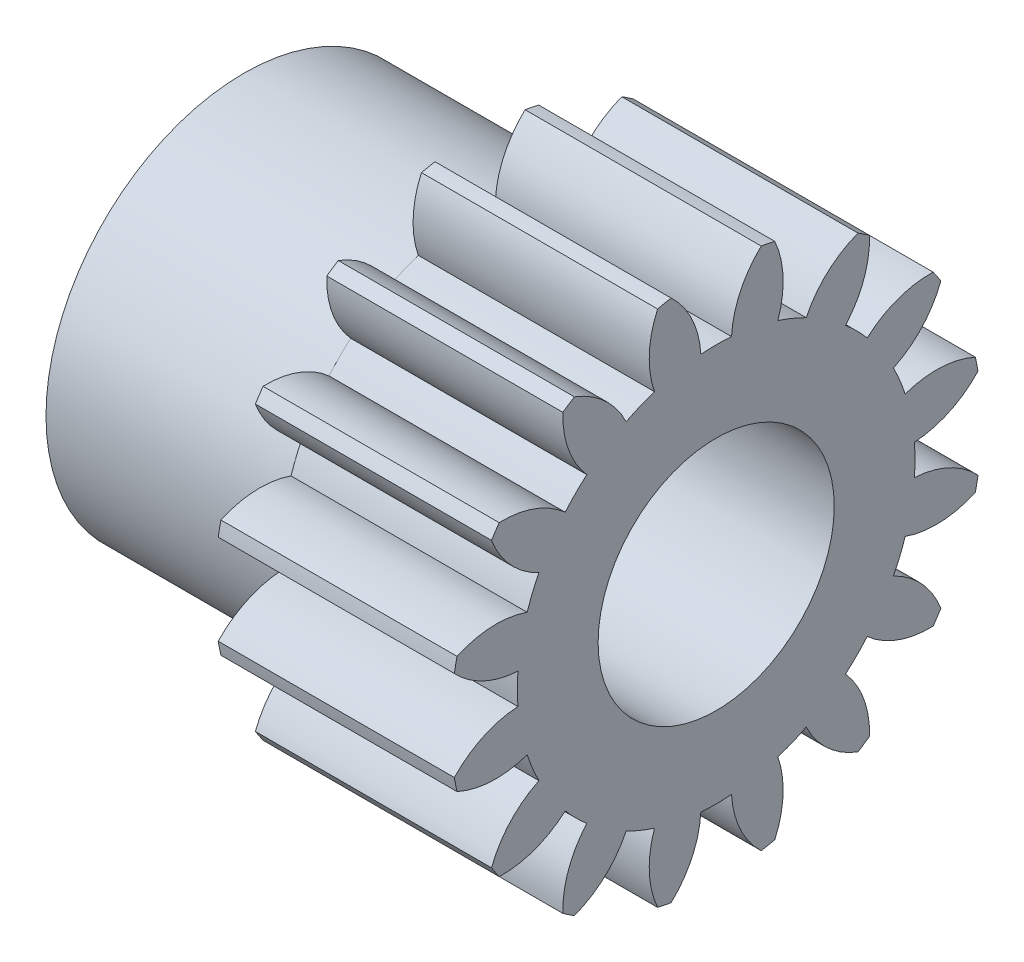
SolidWorks part; units mm, degrees
ref_plane "Plane1" through (0, 0, 0) normal (0, 0, 1) x (1, 0, 0)
ref_plane "Plane2" through (0, 0, 0) normal (0, 1, 0) x (1, 0, 0)
ref_plane "Plane3" through (0, 0, 0) normal (1, 0, 0) x (0, 0, -1)
sketch "HoldingSke" plane through (0, 0, 0) normal (0, 1, 0) x (1, 0, 0)
  line L0 (0, 0) -> (781.3135, -224.038)
  line L1 (-15, 0) -> (100, 0) construction
  line L2 (0, 0) -> (-2.1039, 2.3779)
  line L3 (0, 0) -> (-11.863, 4.5341)
  line L4 (0, 0) -> (8.3015, 2.3804)
  line L5 (0, 0) -> (-5.9497, -2.219)
  line L6 (0, 0) -> (-5.2639, -3.5516)
  line L7 (-2.1039, 2.3779) -> (-0.737, 8.5791)
  line L8 (-76.2, 54.61) -> (-69.596, 54.61)
  line L9 (-71.009, 38.7566) -> (-53.1078, 45.2721)
  line L10 (-76.2, 71.12) -> (104.1128, 71.12)
  line L11 (0, 0) -> (-6.35, 0)
  line L12 (-76.2, 101.6) -> (-76.1716, 101.6)
  line L13 (24.9733, 27.94) -> (52.9518, 28.4284)
  line L14 (24.9733, 27.94) -> (25.0241, 27.9398)
  line L15 (24.9733, 27.94) -> (100.4021, 29.52)
  circle A0 centre (0, 0) radius 3.175
  circle A1 centre (0, 0) radius 5.3213
  circle A2 centre (0, 0) radius 5.3213
  circle A3 centre (0, 0) radius 3.175
  dimension "MHD" = 10.6426
  dimension "Hub_dia" = 10.6426
  dimension "Bore" = 6.35
  dimension "MBD" = 6.35
  dimension "Num_teeth" = 16
  dimension "Pitch_radius" = 180.3128
  dimension "Pitch" = 812.8
  dimension "Width" = 6.35
  dimension "Overall_len" = 6.35
  dimension "Show_teeth" = 16
  dimension "Thickness" = 6.35
  dimension "OAL" = 6.3501
  dimension "T_dim" = 6.604
  dimension "Ap" = 20
  dimension "H" = 19.05
  dimension "Backlash" = 0.0284
  dimension "Addendum_fac" = 1
  dimension "Dedendum_fac" = 1.2
  dimension "Clearance_fac" = 0.2
  dimension "Dedendum_add" = 0.0508
sketch "BasProSke" plane through (0, 0, 0) normal (0, 1, 0) x (1, 0, 0)
  line L0 (-10, 0) -> (60, 0) construction
  line L1 (0, 0) -> (0, 7.1438)
  line L2 (0, 0) -> (6.35, 0)
  line L3 (6.35, 0) -> (6.35, 7.1438)
  line L4 (6.35, 7.1438) -> (0, 7.1438)
  dimension "Diameter" = 14.2875
  dimension "Thickness" = 6.35
revolve "Base-Revolve" add sketch "BasProSke" angle 360 about L0
sketch "TooCutSke" plane through (0, 0, 0) normal (1, 0, 0) x (0, 0, -1)
  line L1 (0, 0) -> (0, 107) construction
  line L2 (0, 0) -> (-0.6722, 6.3143) construction
  line L3 (0, 0) -> (-2.4676, 12.4052) construction
  line L4 (-0.6722, 6.3143) -> (-1.2338, 6.2026) construction
  arc A0 (0.4126, 5.3308) -> (-0.4126, 5.3308) centre (0, 0) ccw
  arc A1 (1.2345, 7.0621) -> (-1.2345, 7.0621) centre (0, 0) ccw
  circle A2 centre (0, 0) radius 6.35 construction
  circle A3 centre (0, 0) radius 5.967 construction
  arc A4 (-0.4126, 5.3308) -> (-1.2345, 7.0621) centre (-2.9486, 5.1876) ccw
  arc A5 (1.2345, 7.0621) -> (0.4126, 5.3308) centre (2.9486, 5.1876) ccw
  dimension "Root_dia" = 10.6934
  dimension "Overcut_dia" = 14.3383
  dimension "Pitch_dia" = 12.7
  dimension "Base_dia" = 11.9341
  dimension "Flank_rad" = 2.54
  dimension "Half_ang" = 11.25
  dimension "Half_CT" = 0.5726
extrude "ToothCut" cut sketch "TooCutSke" along normal through all
fillet "Breaks" [suppressed] radius 0.0159
fillet "RootFillets" [suppressed] radius 0.2095
pattern_circular "TeethCuts" count 16 every 22.5 about axis through (-10, 0, 0) along (1, 0, 0) of "ToothCut", "RootFillets", "Breaks"
sketch "HubNeaOneSke" plane through (0, 0, 0) normal (-1, 0, 0) x (0, 0, 1)
  circle A0 centre (0, 0) radius 5.3213
  dimension "Diameter" = 10.6426
extrude "HubNearOne" add sketch "HubNeaOneSke" along normal blind 6.3501
sketch "HubNeaBotSke" plane through (0, 0, 0) normal (-1, 0, 0) x (0, 0, 1)
  circle A0 centre (0, 0) radius 5.3213
  dimension "Diameter" = 10.6426
extrude "HubNearBoth" [suppressed] add sketch "HubNeaBotSke" along normal blind 3.175
ref_plane "FarPln" through (6.35, 0, 0) normal (1, 0, 0) x (0, 0, -1)
sketch "HubFarSke" plane through (6.35, 0, 0) normal (1, 0, 0) x (0, 0, -1)
  circle A0 centre (0, 0) radius 5.3213
  dimension "Diameter" = 10.6426
extrude "HubFar" [suppressed] add sketch "HubFarSke" along normal blind 3.175
sketch "BorSke" plane through (0, 0, 0) normal (1, 0, 0) x (0, 0, -1)
  circle A0 centre (0, 0) radius 3.175
  dimension "Diameter" = 6.35
extrude "Bore" cut sketch "BorSke" along normal mid plane 12.7001
sketch "KeySke" plane through (0, 0, 0) normal (1, 0, 0) x (0, 0, -1)
  line L0 (-0.127, 0) -> (-0.127, 3.429)
  line L1 (-0.127, 3.429) -> (0.127, 3.429)
  line L2 (0.127, 3.429) -> (0.127, 0)
  line L3 (0, 0) -> (0, 34) construction
  line L4 (-0.127, 0) -> (0.127, 0)
  dimension "Offset" = 3.429
  dimension "Width" = 0.254
extrude "Keyway" [suppressed] cut sketch "KeySke" along normal mid plane 12.7001
pattern_circular "Keyway2" [suppressed] count 2 every 90 about axis through (-10, 0, 0) along (1, 0, 0)
equation "' \"Pitch@HoldingSke\" = 4"
equation "' \"Num_teeth@HoldingSke\" = 12"
equation "' \"Ap@HoldingSke\" =  20"
equation "' \"Width@HoldingSke\" = 0.5"
equation "' \"Hub_dia@HoldingSke\"= 1"
equation "' \"Overall_len@HoldingSke\" = 1.0"
equation "' \"Bore@HoldingSke\" = 0.75"
equation "' \"T_dim@HoldingSke\" = 0.85"
equation "' \"Width@KeySke\" = 0.25"
equation "' \"Show_teeth@HoldingSke\" = 13"
equation "' \"Backlash@HoldingSke\" = 0.009"
equation "' \"Addendum_fac@HoldingSke\" = 1.0"
equation "' \"Dedendum_fac@HoldingSke\" = 1.25"
equation "' \"Dedendum_add@HoldingSke\" = 0.00005"
equation "' \"Clearance_fac@HoldingSke\" = 0.25"
equation "' \"Pitch@HoldingSke\" = 0.5"
equation "' \"Num_teeth@HoldingSke\" = 23"
equation "' \"Show_teeth@HoldingSke\" = 23"
equation "' \"Backlash@HoldingSke\" = 0.0375"
equation "\"Overcut_dia@TooCutSke\" = (\"Num_teeth@HoldingSke\" + 2 * \"Addendum_fac@HoldingSke\") / \"Pitch@HoldingSke\" + 0.002"
equation "\"Pitch_dia@TooCutSke\" = \"Num_teeth@HoldingSke\" / \"Pitch@HoldingSke\""
equation "\"Base_dia@TooCutSke\" = \"Num_teeth@HoldingSke\" / \"Pitch@HoldingSke\" * cos((\"Ap@HoldingSke\"  * 3.14159265 / 180))"
equation "\"Root_dia@TooCutSke\" = (\"Num_teeth@HoldingSke\" + 2) / \"Pitch@HoldingSke\" - 2 * (\"Addendum_fac@HoldingSke\" + \"Dedendum_fac@HoldingSke\") / \"Pitch@HoldingSke\" - \"Dedendum_add@HoldingSke\" * 2"
equation "\"Half_ang@TooCutSke\" = 180 / \"Num_teeth@HoldingSke\""
equation "\"Half_CT@TooCutSke\" = \"Num_teeth@HoldingSke\" / \"Pitch@HoldingSke\" * sin((3.14159265 / 2 / \"Num_teeth@HoldingSke\")) / 2 - 7 * \"Backlash@HoldingSke\" / 4"
equation "\"Flank_rad@TooCutSke\" = \"Num_teeth@HoldingSke\" / \"Pitch@HoldingSke\" / 5"
equation "\"Radius@RootFillets\" = \"Clearance_fac@HoldingSke\" / \"Pitch@HoldingSke\" + \"Dedendum_add@HoldingSke\""
equation "\"Break_rad@Breaks\" = 0.02 / \"Pitch@HoldingSke\""
equation "\"Thickness@HoldingSke\" = \"Width@HoldingSke\""
equation "\"OAL@HoldingSke\" = \"Thickness@HoldingSke\""
equation "\"MHD@HoldingSke\" = (\"Num_teeth@HoldingSke\" + 2) / \"Pitch@HoldingSke\" - 2 * (\"Addendum_fac@HoldingSke\" + \"Dedendum_fac@HoldingSke\")  / \"Pitch@HoldingSke\" - \"Dedendum_add@HoldingSke\" * 2"
equation "\"MBD@HoldingSke\" = (\"Num_teeth@HoldingSke\" + 2) / \"Pitch@HoldingSke\" - 2 * (\"Addendum_fac@HoldingSke\" + \"Dedendum_fac@HoldingSke\")  / \"Pitch@HoldingSke\" - \"Dedendum_add@HoldingSke\" * 2 - 0.002"
equation "\"MHD@HoldingSke\" = ((sgn( \"MHD@HoldingSke\" - \"Hub_dia@HoldingSke\" )-1)*( \"MHD@HoldingSke\" - \"Hub_dia@HoldingSke\" ))/-2+ \"Hub_dia@HoldingSke\""
equation "\"MBD@HoldingSke\" = ((sgn( \"MBD@HoldingSke\" - \"Bore@HoldingSke\" )-1)*( \"MBD@HoldingSke\" - \"Bore@HoldingSke\" ))/-2+ \"Bore@HoldingSke\""
equation "\"OAL@HoldingSke\" = ((sgn( \"OAL@HoldingSke\" - \"Overall_len@HoldingSke\" )+1)*( \"OAL@HoldingSke\" - \"Overall_len@HoldingSke\" ))/2 + \"Overall_len@HoldingSke\" + 0.000002"
equation "\"Num_teeth@TeethCuts\" = int( \"Show_teeth@HoldingSke\" ) + 1"
equation "\"Num_teeth@TeethCuts\" = ((sgn( \"Num_teeth@TeethCuts\" - \"Num_teeth@HoldingSke\" )-1)*( \"Num_teeth@TeethCuts\" - \"Num_teeth@HoldingSke\" ))/-2+ \"Num_teeth@HoldingSke\""
equation "\"Num_teeth@TeethCuts\" = ((sgn( \"Num_teeth@TeethCuts\" - 2.0)+1)*( \"Num_teeth@TeethCuts\" - 2.0))/2 +2.0"
equation "\"Angle@TeethCuts\" = 360.0 / \"Num_teeth@HoldingSke\""
equation "\"Diameter@BasProSke\" = (\"Num_teeth@HoldingSke\" + 2 * \"Addendum_fac@HoldingSke\") / \"Pitch@HoldingSke\""
equation "\"Thickness@BasProSke\"  = \"Thickness@HoldingSke\""
equation "' \"Fillet_rad@BasProSke\" =  \"Thickness@HoldingSke\" * 0.05"
equation "\"MHD@HoldingSke\" = ((sgn( \"MHD@HoldingSke\" - \"Root_dia@TooCutSke\" )-1)*( \"MHD@HoldingSke\" - \"Root_dia@TooCutSke\" ))/-2+ \"Root_dia@TooCutSke\""
equation "\"Diameter@HubNeaOneSke\" = \"MHD@HoldingSke\""
equation "\"Length@HubNearOne\" = \"OAL@HoldingSke\" - \"Thickness@BasProSke\""
equation "\"Diameter@HubNeaBotSke\" = \"MHD@HoldingSke\""
equation "\"Length@HubNearBoth\" = ( \"OAL@HoldingSke\" - \"Thickness@BasProSke\" ) / 2.0"
equation "\"Thickness@FarPln\" = \"Thickness@BasProSke\""
equation "\"Diameter@HubFarSke\" = \"MHD@HoldingSke\""
equation "\"Length@HubFar\" = ( \"OAL@HoldingSke\" - \"Thickness@BasProSke\" ) / 2.0"
equation "\"Diameter@BorSke\" = \"MBD@HoldingSke\""
equation "\"D1@Bore\" = \"OAL@HoldingSke\" * 2.0"
equation "\"D1@Keyway\" = \"OAL@HoldingSke\" * 2.0"
equation "\"Offset@KeySke\" = \"T_dim@HoldingSke\" - \"MBD@HoldingSke\" / 2.0"
